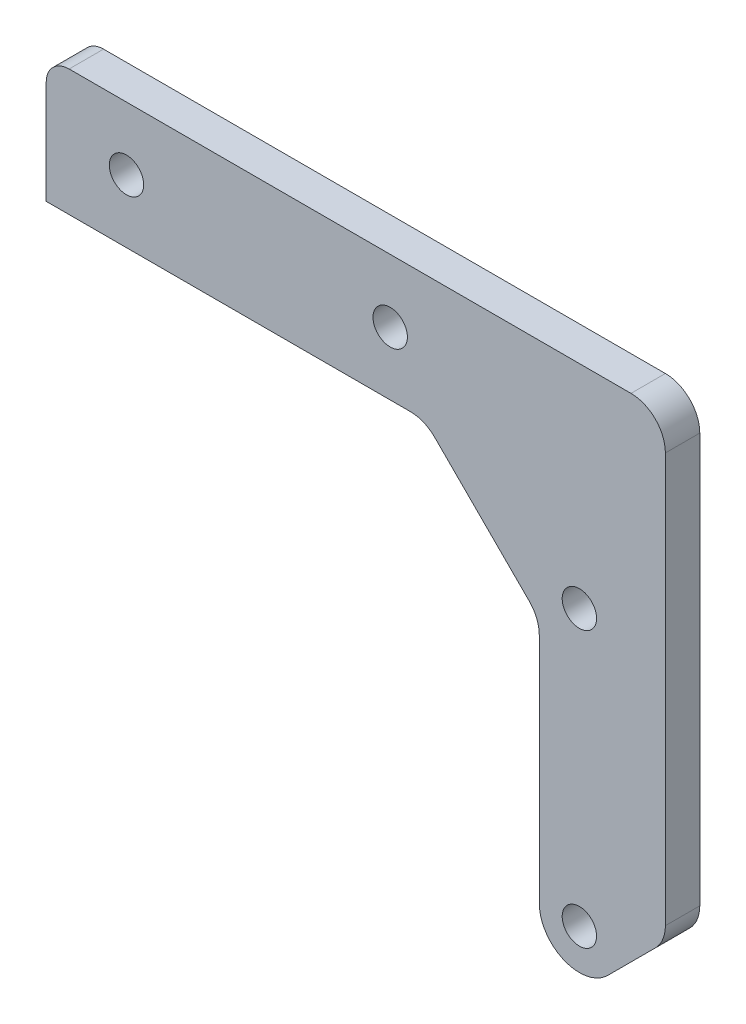
SolidWorks part; units mm, degrees
ref_plane "Спереди" through (0, 0, 0) normal (0, 0, 1) x (1, 0, 0)
ref_plane "Сверху" through (0, 0, 0) normal (0, 1, 0) x (1, 0, 0)
ref_plane "Справа" through (0, 0, 0) normal (1, 0, 0) x (0, 0, -1)
sketch "Эскиз1" plane through (0, 0, 0) normal (0, 0, 1) x (1, 0, 0)
  line L0 (-48.5, 0) -> (5.5, 0) construction
  line L1 (-2, 5.5) -> (-2, -46.5) construction
  line L2 (-48.5, 5.5) -> (-48.5, -5.5)
  line L3 (-48.5, -5.5) -> (-15.5, -5.5)
  line L4 (-5.5, -46.5) -> (5.5, -46.5) construction
  line L5 (-5.5, -15.5) -> (-5.5, -37)
  line L6 (5.5, -34.4497) -> (5.5, 5.5)
  line L7 (5.5, 5.5) -> (-48.5, 5.5)
  line L8 (-15.5, -5.5) -> (-5.5, -15.5)
  line L9 (0, 5.5) -> (0, -46.5) construction
  line L10 (0.4749, -39.4749) -> (5.5, -34.4497)
  line L11 (-5.5, -37) -> (-5.5, -46.5) construction
  line L12 (5.5, -34.4497) -> (5.5, -46.5) construction
  arc A0 (-5.5, -37) -> (0.4749, -39.4749) centre (-2, -37) ccw
  circle A4 centre (-18.5, 0) radius 1.5
  circle A5 centre (-41.5, 0) radius 1.5
  circle A6 centre (-2, -13) radius 1.5
  circle A7 centre (-2, -37) radius 1.5
  dimension "D4" = 11
  dimension "D7" = 13
  dimension "D12" = 3
  dimension "D10" = 45
  dimension "D1" = 11
  dimension "D2" = 43
  dimension "D3" = 52
  dimension "D5" = 10
  dimension "D6" = 45
  dimension "D8" = 3.5
  dimension "D9" = 7
  dimension "D11" = 23
  dimension "D16" = 24
extrude "тело" add sketch "Эскиз1" along normal blind 3
fillet "Fillet1" radius 3
fillet "Скругление1" radius 2
chamfer "Фаски под шляпки (левая)" [suppressed] distance 1.5 angle 45
chamfer "Фаски под шляпки (правая)" [suppressed] distance 1.5 angle 45
